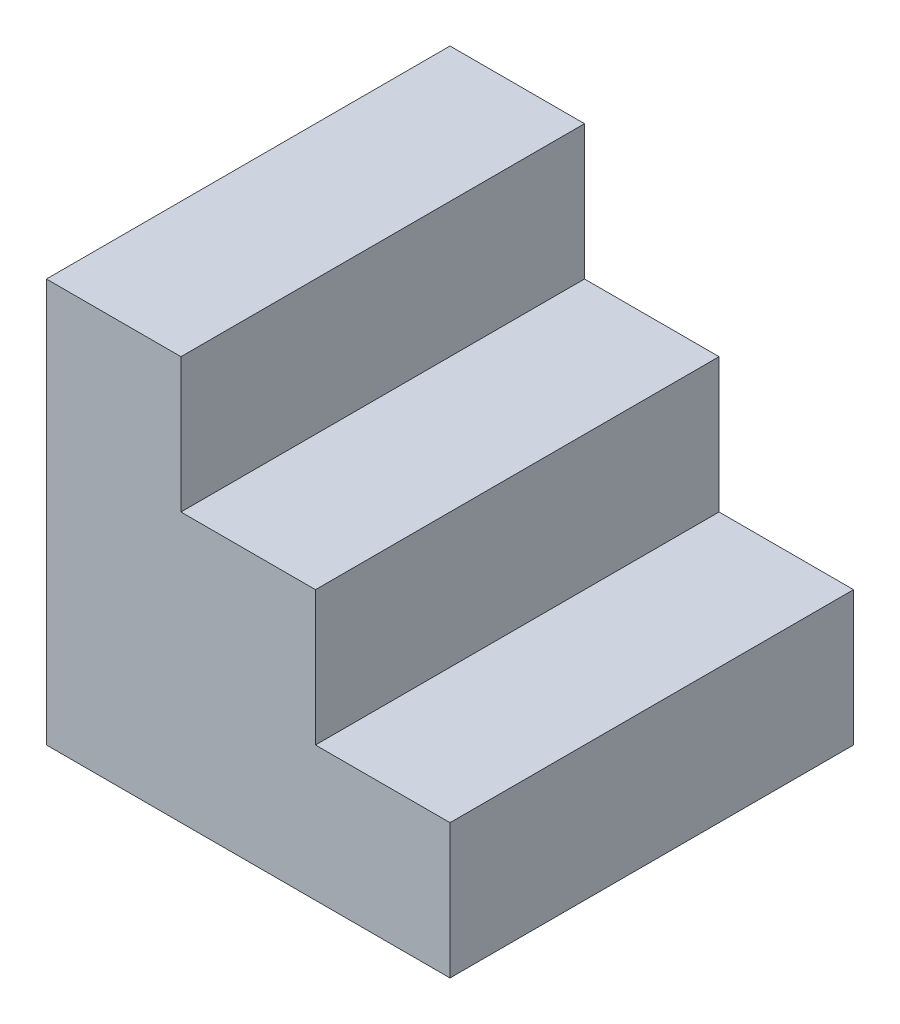
SolidWorks part; units mm, degrees
ref_plane "Front Plane" through (0, 0, 0) normal (0, 0, 1) x (1, 0, 0)
ref_plane "Top Plane" through (0, 0, 0) normal (0, 1, 0) x (1, 0, 0)
ref_plane "Right Plane" through (0, 0, 0) normal (1, 0, 0) x (0, 0, -1)
sketch "Esquisse1" plane through (0, 0, 0) normal (0, 0, 1) x (1, 0, 0)
  line L0 (0, 0) -> (100, 0)
  line L1 (100, 0) -> (100, 33.3333)
  line L2 (100, 33.3333) -> (66.6667, 33.3333)
  line L3 (66.6667, 33.3333) -> (66.6667, 66.6667)
  line L4 (66.6667, 66.6667) -> (33.3333, 66.6667)
  line L5 (33.3333, 66.6667) -> (33.3333, 100)
  line L6 (33.3333, 100) -> (0, 100)
  line L7 (0, 100) -> (0, 0)
  dimension "D1" = 100
  dimension "D2" = 100
extrude "Extrusion1" add sketch "Esquisse1" along normal blind 100 contours L6 L7 L0 L1 L2 L3 L4 L5
